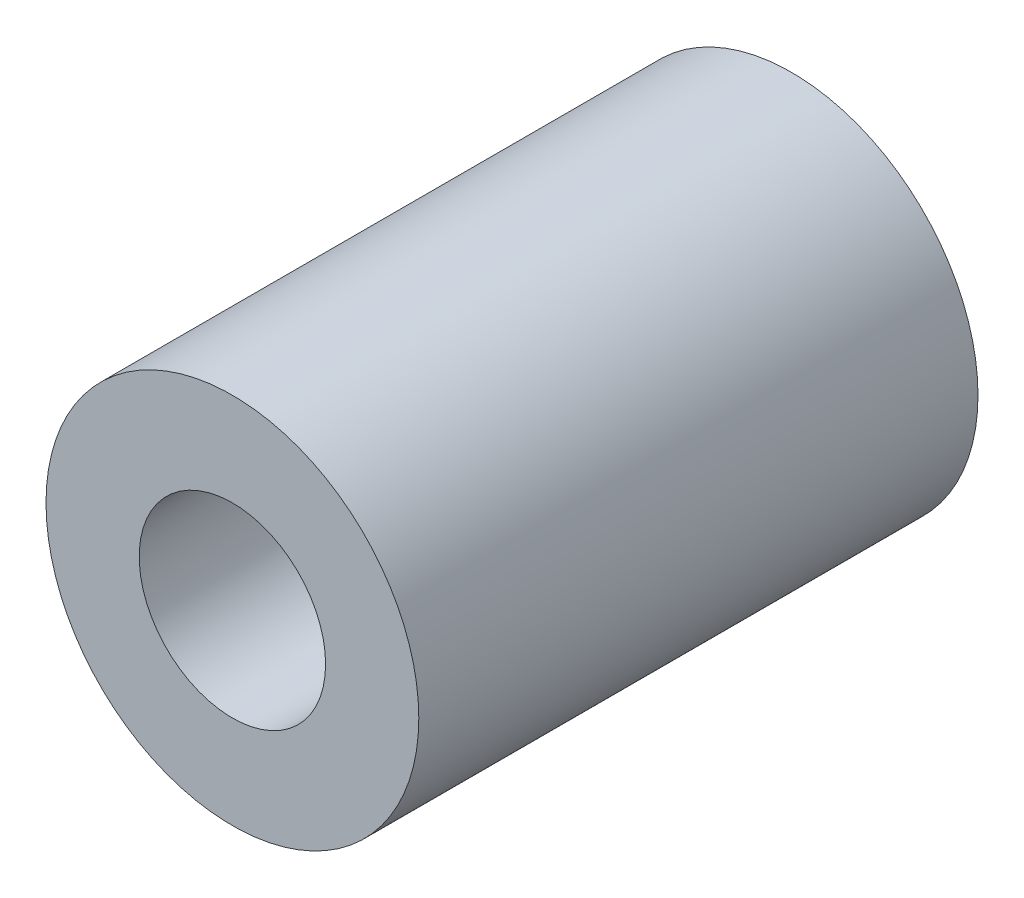
SolidWorks part; units mm, degrees
ref_plane "Front Plane" through (0, 0, 0) normal (0, 0, 1) x (1, 0, 0)
ref_plane "Top Plane" through (0, 0, 0) normal (0, 1, 0) x (1, 0, 0)
ref_plane "Right Plane" through (0, 0, 0) normal (1, 0, 0) x (0, 0, -1)
sketch "Sketch1" plane through (0, 0, 0) normal (0, 0, 1) x (1, 0, 0)
  circle A0 centre (0, 0) radius 5
  circle A1 centre (0, 0) radius 2.5
  dimension "D1" = 10
  dimension "D2" = 5
extrude "Boss-Extrude1" add sketch "Sketch1" along normal blind 15
